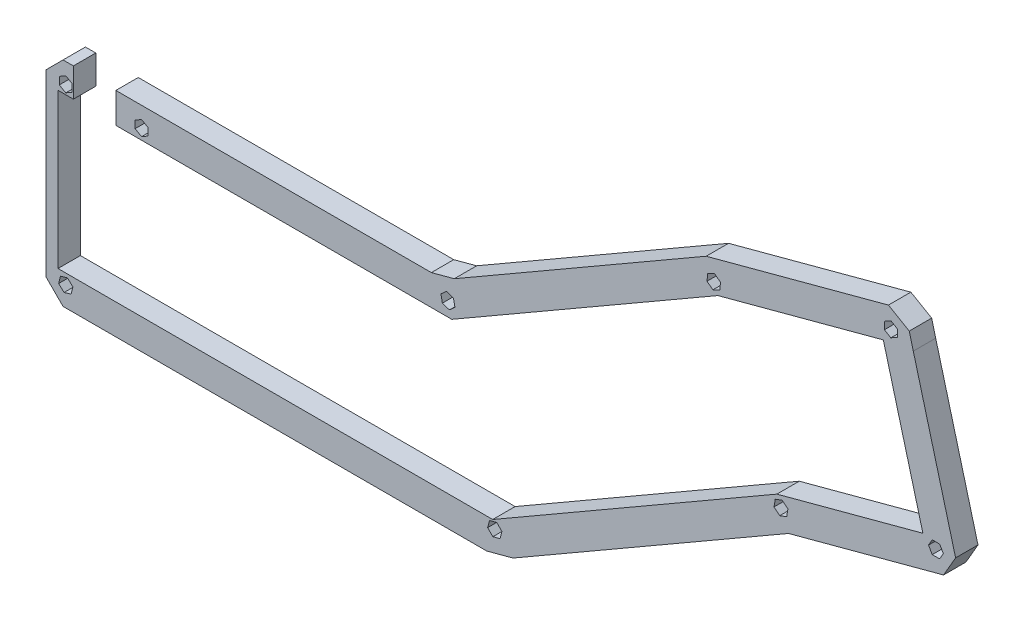
SolidWorks part; units mm, degrees
ref_plane "Plan de face" through (0, 0, 0) normal (0, 0, 1) x (1, 0, 0)
ref_plane "Plan de dessus" through (0, 0, 0) normal (0, 1, 0) x (1, 0, 0)
ref_plane "Plan de droite" through (0, 0, 0) normal (1, 0, 0) x (0, 0, -1)
sketch "Esquisse1" plane through (0, 0, 0) normal (0, 0, 1) x (1, 0, 0)
  line L0 (-73.9886, 18.0851) -> (-59.9886, 18.0851) construction
  line L1 (-73.9886, 37.0851) -> (-59.9886, 37.0851) construction
  line L2 (-73.9886, 37.0851) -> (-73.9886, 23.0851) construction
  line L3 (-73.9886, 23.0851) -> (-59.9886, 23.0851) construction
  line L4 (-59.9886, 37.0851) -> (-59.9886, 23.0851) construction
  line L5 (-73.9886, 18.0851) -> (-73.9886, 4.0851) construction
  line L6 (-73.9886, 4.0851) -> (-59.9886, 4.0851) construction
  line L7 (-59.9886, 18.0851) -> (-59.9886, 4.0851) construction
  line L8 (-73.9886, -0.9149) -> (-59.9886, -0.9149) construction
  line L9 (-73.9886, -0.9149) -> (-73.9886, -14.9149) construction
  line L10 (-73.9886, -14.9149) -> (-59.9886, -14.9149) construction
  line L11 (-59.9886, -0.9149) -> (-59.9886, -14.9149) construction
  line L12 (-73.9886, 37.0851) -> (-73.9886, 18.0851) construction
  line L13 (-54.9886, 18.0851) -> (-40.9886, 18.0851) construction
  line L14 (-54.9886, 37.0851) -> (-40.9886, 37.0851) construction
  line L15 (-54.9886, 37.0851) -> (-54.9886, 23.0851) construction
  line L16 (-54.9886, 23.0851) -> (-40.9886, 23.0851) construction
  line L17 (-40.9886, 37.0851) -> (-40.9886, 23.0851) construction
  line L18 (-54.9886, 18.0851) -> (-54.9886, 4.0851) construction
  line L19 (-54.9886, 4.0851) -> (-40.9886, 4.0851) construction
  line L20 (-40.9886, 18.0851) -> (-40.9886, 4.0851) construction
  line L21 (-54.9886, -0.9149) -> (-40.9886, -0.9149) construction
  line L22 (-54.9886, -0.9149) -> (-54.9886, -14.9149) construction
  line L23 (-54.9886, -14.9149) -> (-40.9886, -14.9149) construction
  line L24 (-40.9886, -0.9149) -> (-40.9886, -14.9149) construction
  line L25 (-54.9886, 37.0851) -> (-54.9886, 18.0851) construction
  line L26 (-35.9886, 18.0851) -> (-21.9886, 18.0851) construction
  line L27 (-35.9886, 37.0851) -> (-21.9886, 37.0851) construction
  line L28 (-35.9886, 37.0851) -> (-35.9886, 23.0851) construction
  line L29 (-35.9886, 23.0851) -> (-21.9886, 23.0851) construction
  line L30 (-21.9886, 37.0851) -> (-21.9886, 23.0851) construction
  line L31 (-35.9886, 18.0851) -> (-35.9886, 4.0851) construction
  line L32 (-35.9886, 4.0851) -> (-21.9886, 4.0851) construction
  line L33 (-21.9886, 18.0851) -> (-21.9886, 4.0851) construction
  line L34 (-35.9886, -0.9149) -> (-21.9886, -0.9149) construction
  line L35 (-35.9886, -0.9149) -> (-35.9886, -14.9149) construction
  line L36 (-35.9886, -14.9149) -> (-21.9886, -14.9149) construction
  line L37 (-21.9886, -0.9149) -> (-21.9886, -14.9149) construction
  line L38 (-35.9886, 37.0851) -> (-35.9886, 18.0851) construction
  line L39 (-16.9886, 18.0851) -> (-2.9886, 18.0851) construction
  line L40 (-16.9886, 37.0851) -> (-2.9886, 37.0851) construction
  line L41 (-16.9886, 37.0851) -> (-16.9886, 23.0851) construction
  line L42 (-16.9886, 23.0851) -> (-2.9886, 23.0851) construction
  line L43 (-2.9886, 37.0851) -> (-2.9886, 23.0851) construction
  line L44 (-16.9886, 18.0851) -> (-16.9886, 4.0851) construction
  line L45 (-16.9886, 4.0851) -> (-2.9886, 4.0851) construction
  line L46 (-2.9886, 18.0851) -> (-2.9886, 4.0851) construction
  line L47 (-16.9886, -0.9149) -> (-2.9886, -0.9149) construction
  line L48 (-16.9886, -0.9149) -> (-16.9886, -14.9149) construction
  line L49 (-16.9886, -14.9149) -> (-2.9886, -14.9149) construction
  line L50 (-2.9886, -0.9149) -> (-2.9886, -14.9149) construction
  line L51 (-16.9886, 37.0851) -> (-16.9886, 18.0851) construction
  line L52 (2.0114, 18.0851) -> (16.0114, 18.0851) construction
  line L53 (2.0114, 37.0851) -> (16.0114, 37.0851) construction
  line L54 (2.0114, 37.0851) -> (2.0114, 23.0851) construction
  line L55 (2.0114, 23.0851) -> (16.0114, 23.0851) construction
  line L56 (16.0114, 37.0851) -> (16.0114, 23.0851) construction
  line L57 (2.0114, 18.0851) -> (2.0114, 4.0851) construction
  line L58 (2.0114, 4.0851) -> (16.0114, 4.0851) construction
  line L59 (16.0114, 18.0851) -> (16.0114, 4.0851) construction
  line L60 (2.0114, -0.9149) -> (16.0114, -0.9149) construction
  line L61 (2.0114, -0.9149) -> (2.0114, -14.9149) construction
  line L62 (2.0114, -14.9149) -> (16.0114, -14.9149) construction
  line L63 (16.0114, -0.9149) -> (16.0114, -14.9149) construction
  line L64 (2.0114, 37.0851) -> (2.0114, 18.0851) construction
  line L65 (21.0114, 18.0851) -> (35.0114, 18.0851) construction
  line L66 (21.0114, 37.0851) -> (35.0114, 37.0851) construction
  line L67 (21.0114, 37.0851) -> (21.0114, 23.0851) construction
  line L68 (21.0114, 23.0851) -> (35.0114, 23.0851) construction
  line L69 (35.0114, 37.0851) -> (35.0114, 23.0851) construction
  line L70 (21.0114, 18.0851) -> (21.0114, 4.0851) construction
  line L71 (21.0114, 4.0851) -> (35.0114, 4.0851) construction
  line L72 (35.0114, 18.0851) -> (35.0114, 4.0851) construction
  line L73 (21.0114, -0.9149) -> (35.0114, -0.9149) construction
  line L74 (21.0114, -0.9149) -> (21.0114, -14.9149) construction
  line L75 (21.0114, -14.9149) -> (35.0114, -14.9149) construction
  line L76 (35.0114, -0.9149) -> (35.0114, -14.9149) construction
  line L77 (21.0114, 37.0851) -> (21.0114, 18.0851) construction
  line L78 (40.0114, 18.0851) -> (54.0114, 18.0851) construction
  line L79 (40.0114, 37.0851) -> (54.0114, 37.0851) construction
  line L80 (40.0114, 37.0851) -> (40.0114, 23.0851) construction
  line L81 (40.0114, 23.0851) -> (54.0114, 23.0851) construction
  line L82 (54.0114, 37.0851) -> (54.0114, 23.0851) construction
  line L83 (40.0114, 18.0851) -> (40.0114, 4.0851) construction
  line L84 (40.0114, 4.0851) -> (54.0114, 4.0851) construction
  line L85 (54.0114, 18.0851) -> (54.0114, 4.0851) construction
  line L86 (40.0114, -0.9149) -> (54.0114, -0.9149) construction
  line L87 (40.0114, -0.9149) -> (40.0114, -14.9149) construction
  line L88 (40.0114, -14.9149) -> (54.0114, -14.9149) construction
  line L89 (54.0114, -0.9149) -> (54.0114, -14.9149) construction
  line L90 (40.0114, 37.0851) -> (40.0114, 18.0851) construction
  line L91 (-73.9886, 18.0851) -> (-54.9886, 18.0851) construction
  line L92 (56.0114, 20.0851) -> (56.7532, 18.8002) construction
  line L93 (38.0114, 39.0851) -> (56.0114, 39.0851) construction
  line L94 (56.0114, 39.0851) -> (56.0114, 21.0851) construction
  line L95 (38.0114, 21.0851) -> (56.0114, 21.0851) construction
  line L96 (38.0114, 39.0851) -> (38.0114, 21.0851) construction
  line L97 (19.0114, 39.0851) -> (37.0114, 39.0851) construction
  line L98 (37.0114, 39.0851) -> (37.0114, 21.0851) construction
  line L99 (19.0114, 21.0851) -> (37.0114, 21.0851) construction
  line L100 (19.0114, 39.0851) -> (19.0114, 21.0851) construction
  line L101 (79.4363, 55.512) -> (88.4363, 39.9235) construction
  line L102 (88.4363, 39.9235) -> (72.8478, 30.9235) construction
  line L103 (63.8478, 46.512) -> (72.8478, 30.9235) construction
  line L104 (79.4363, 55.512) -> (63.8478, 46.512) construction
  line L105 (62.9818, 46.012) -> (71.9818, 30.4235) construction
  line L106 (71.9818, 30.4235) -> (56.3933, 21.4235) construction
  line L107 (47.3933, 37.012) -> (56.3933, 21.4235) construction
  line L108 (62.9818, 46.012) -> (47.3933, 37.012) construction
  line L109 (164.5845, 60.0309) -> (148.9961, 51.0309) construction
  line L110 (62.2497, 43.2799) -> (71.7497, 26.8254) construction
  line L111 (78.7042, 52.7799) -> (88.2042, 36.3254) construction
  line L112 (95.1587, 62.2799) -> (104.6587, 45.8254) construction
  line L113 (111.6132, 71.7799) -> (121.1132, 55.3254) construction
  line L114 (128.0677, 81.2799) -> (137.5677, 64.8254) construction
  line L115 (144.5221, 90.7799) -> (154.0221, 74.3254) construction
  line L116 (148.9961, 51.0309) -> (157.6657, 36.0146) construction
  line L117 (69.1254, 3.371) -> (76.1254, -8.7534) construction
  line L118 (88.2497, -1.7534) -> (76.1254, -8.7534) construction
  line L119 (81.2497, 10.371) -> (88.2497, -1.7534) construction
  line L120 (81.2497, 10.371) -> (69.1254, 3.371) construction
  line L121 (59.6254, 19.8254) -> (66.6254, 7.7011) construction
  line L122 (78.7497, 14.7011) -> (66.6254, 7.7011) construction
  line L123 (71.7497, 26.8254) -> (78.7497, 14.7011) construction
  line L124 (50.1254, 36.2799) -> (57.1254, 24.1556) construction
  line L125 (69.2497, 31.1556) -> (57.1254, 24.1556) construction
  line L126 (62.2497, 43.2799) -> (69.2497, 31.1556) construction
  line L127 (62.2497, 43.2799) -> (50.1254, 36.2799) construction
  line L128 (71.7497, 26.8254) -> (59.6254, 19.8254) construction
  line L129 (85.5799, 12.871) -> (92.5799, 0.7466) construction
  line L130 (104.7042, 7.7466) -> (92.5799, 0.7466) construction
  line L131 (97.7042, 19.871) -> (104.7042, 7.7466) construction
  line L132 (97.7042, 19.871) -> (85.5799, 12.871) construction
  line L133 (76.0799, 29.3254) -> (83.0799, 17.2011) construction
  line L134 (95.2042, 24.2011) -> (83.0799, 17.2011) construction
  line L135 (88.2042, 36.3254) -> (95.2042, 24.2011) construction
  line L136 (66.5799, 45.7799) -> (73.5799, 33.6556) construction
  line L137 (85.7042, 40.6556) -> (73.5799, 33.6556) construction
  line L138 (78.7042, 52.7799) -> (85.7042, 40.6556) construction
  line L139 (78.7042, 52.7799) -> (66.5799, 45.7799) construction
  line L140 (88.2042, 36.3254) -> (76.0799, 29.3254) construction
  line L141 (102.0343, 22.371) -> (109.0343, 10.2466) construction
  line L142 (121.1587, 17.2466) -> (109.0343, 10.2466) construction
  line L143 (114.1587, 29.371) -> (121.1587, 17.2466) construction
  line L144 (114.1587, 29.371) -> (102.0343, 22.371) construction
  line L145 (92.5343, 38.8254) -> (99.5343, 26.7011) construction
  line L146 (111.6587, 33.7011) -> (99.5343, 26.7011) construction
  line L147 (104.6587, 45.8254) -> (111.6587, 33.7011) construction
  line L148 (83.0343, 55.2799) -> (90.0343, 43.1556) construction
  line L149 (102.1587, 50.1556) -> (90.0343, 43.1556) construction
  line L150 (95.1587, 62.2799) -> (102.1587, 50.1556) construction
  line L151 (95.1587, 62.2799) -> (83.0343, 55.2799) construction
  line L152 (104.6587, 45.8254) -> (92.5343, 38.8254) construction
  line L153 (118.4888, 31.871) -> (125.4888, 19.7466) construction
  line L154 (137.6132, 26.7466) -> (125.4888, 19.7466) construction
  line L155 (130.6132, 38.871) -> (137.6132, 26.7466) construction
  line L156 (130.6132, 38.871) -> (118.4888, 31.871) construction
  line L157 (108.9888, 48.3254) -> (115.9888, 36.2011) construction
  line L158 (128.1132, 43.2011) -> (115.9888, 36.2011) construction
  line L159 (121.1132, 55.3254) -> (128.1132, 43.2011) construction
  line L160 (99.4888, 64.7799) -> (106.4888, 52.6556) construction
  line L161 (118.6132, 59.6556) -> (106.4888, 52.6556) construction
  line L162 (111.6132, 71.7799) -> (118.6132, 59.6556) construction
  line L163 (111.6132, 71.7799) -> (99.4888, 64.7799) construction
  line L164 (121.1132, 55.3254) -> (108.9888, 48.3254) construction
  line L165 (134.9433, 41.371) -> (141.9433, 29.2466) construction
  line L166 (154.0677, 36.2466) -> (141.9433, 29.2466) construction
  line L167 (147.0677, 48.371) -> (154.0677, 36.2466) construction
  line L168 (147.0677, 48.371) -> (134.9433, 41.371) construction
  line L169 (125.4433, 57.8254) -> (132.4433, 45.7011) construction
  line L170 (144.5677, 52.7011) -> (132.4433, 45.7011) construction
  line L171 (137.5677, 64.8254) -> (144.5677, 52.7011) construction
  line L172 (115.9433, 74.2799) -> (122.9433, 62.1556) construction
  line L173 (135.0677, 69.1556) -> (122.9433, 62.1556) construction
  line L174 (128.0677, 81.2799) -> (135.0677, 69.1556) construction
  line L175 (128.0677, 81.2799) -> (115.9433, 74.2799) construction
  line L176 (137.5677, 64.8254) -> (125.4433, 57.8254) construction
  line L177 (151.7281, 50.2988) -> (158.3978, 38.7466) construction
  line L178 (170.5221, 45.7466) -> (158.3978, 38.7466) construction
  line L179 (163.8525, 57.2988) -> (170.5221, 45.7466) construction
  line L180 (163.8525, 57.2988) -> (151.7281, 50.2988) construction
  line L181 (141.8978, 67.3254) -> (148.8978, 55.2011) construction
  line L182 (161.0221, 62.2011) -> (148.8978, 55.2011) construction
  line L183 (154.0221, 74.3254) -> (161.0221, 62.2011) construction
  line L184 (132.3978, 83.7799) -> (139.3978, 71.6556) construction
  line L185 (151.5221, 78.6556) -> (139.3978, 71.6556) construction
  line L186 (144.5221, 90.7799) -> (151.5221, 78.6556) construction
  line L187 (144.5221, 90.7799) -> (132.3978, 83.7799) construction
  line L188 (154.0221, 74.3254) -> (141.8978, 67.3254) construction
  line L189 (173.2542, 45.0146) -> (157.6657, 36.0146) construction
  line L190 (164.5845, 60.0309) -> (173.2542, 45.0146) construction
  line L191 (178.3169, 34.0986) -> (169.0534, 56.4627) construction
  line L192 (169.6903, 62.1458) -> (174.1781, 45.3972) construction
  line L193 (174.1781, 45.3972) -> (191.5647, 50.056) construction
  line L194 (187.077, 66.8045) -> (191.5647, 50.056) construction
  line L195 (162.1337, 98.0749) -> (167.0513, 79.7223) construction
  line L196 (169.6903, 62.1458) -> (187.077, 66.8045) construction
  line L197 (167.0513, 79.7223) -> (180.5742, 83.3457) construction
  line L198 (162.1337, 98.0749) -> (175.6567, 101.6983) construction
  line L199 (162.1337, 98.0749) -> (165.7572, 84.5519) construction
  line L200 (165.7572, 84.5519) -> (179.2801, 88.1754) construction
  line L201 (175.6567, 101.6983) -> (179.2801, 88.1754) construction
  line L202 (167.0513, 79.7223) -> (170.6747, 66.1993) construction
  line L203 (170.6747, 66.1993) -> (184.1977, 69.8228) construction
  line L204 (180.5742, 83.3457) -> (184.1977, 69.8228) construction
  line L205 (172.1398, 60.7315) -> (185.6628, 64.355) construction
  line L206 (172.1398, 60.7315) -> (175.5923, 47.8467) construction
  line L207 (175.5923, 47.8467) -> (189.1152, 51.4702) construction
  line L208 (185.6628, 64.355) -> (189.1152, 51.4702) construction
  line L209 (185.4038, 84.6398) -> (198.9268, 88.2633) construction
  line L210 (180.4863, 102.9924) -> (194.0092, 106.6159) construction
  line L211 (180.4863, 102.9924) -> (184.1097, 89.4695) construction
  line L212 (184.1097, 89.4695) -> (197.6327, 93.0929) construction
  line L213 (194.0092, 106.6159) -> (197.6327, 93.0929) construction
  line L214 (185.4038, 84.6398) -> (189.0273, 71.1169) construction
  line L215 (189.0273, 71.1169) -> (202.5503, 74.7403) construction
  line L216 (198.9268, 88.2633) -> (202.5503, 74.7403) construction
  line L217 (190.4924, 65.6491) -> (204.0154, 69.2726) construction
  line L218 (190.4924, 65.6491) -> (193.9449, 52.7643) construction
  line L219 (193.9449, 52.7643) -> (207.4678, 56.3878) construction
  line L220 (204.0154, 69.2726) -> (207.4678, 56.3878) construction
  line L221 (188.0429, 67.0633) -> (192.5307, 50.3148) construction
  line L222 (192.5307, 50.3148) -> (209.9173, 54.9735) construction
  line L223 (205.4296, 71.7221) -> (209.9173, 54.9735) construction
  line L224 (180.4863, 102.9924) -> (185.4038, 84.6398) construction
  line L225 (188.0429, 67.0633) -> (205.4296, 71.7221) construction
  line L226 (203.7564, 89.5574) -> (217.2794, 93.1809) construction
  line L227 (198.8389, 107.91) -> (212.3618, 111.5335) construction
  line L228 (198.8389, 107.91) -> (202.4623, 94.387) construction
  line L229 (202.4623, 94.387) -> (215.9853, 98.0105) construction
  line L230 (212.3618, 111.5335) -> (215.9853, 98.0105) construction
  line L231 (203.7564, 89.5574) -> (207.3799, 76.0344) construction
  line L232 (207.3799, 76.0344) -> (220.9029, 79.6579) construction
  line L233 (217.2794, 93.1809) -> (220.9029, 79.6579) construction
  line L234 (208.845, 70.5667) -> (222.368, 74.1901) construction
  line L235 (208.845, 70.5667) -> (212.2975, 57.6819) construction
  line L236 (212.2975, 57.6819) -> (225.8204, 61.3053) construction
  line L237 (222.368, 74.1901) -> (225.8204, 61.3053) construction
  line L238 (206.3955, 71.9809) -> (210.8833, 55.2324) construction
  line L239 (210.8833, 55.2324) -> (228.2699, 59.8911) construction
  line L240 (223.7822, 76.6396) -> (228.2699, 59.8911) construction
  line L241 (198.8389, 107.91) -> (203.7564, 89.5574) construction
  line L242 (206.3955, 71.9809) -> (223.7822, 76.6396) construction
  line L243 (167.0513, 79.7223) -> (185.4038, 84.6398) construction
  line L244 (38.0114, 20.0851) -> (56.0114, 20.0851) construction
  line L245 (56.0114, 20.0851) -> (56.0114, 2.0851) construction
  line L246 (38.0114, 2.0851) -> (56.0114, 2.0851) construction
  line L247 (38.0114, 20.0851) -> (38.0114, 2.0851) construction
  line L248 (72.4818, 29.5575) -> (56.8933, 20.5575) construction
  line L249 (56.8933, 20.5575) -> (65.8933, 4.969) construction
  line L250 (81.4818, 13.969) -> (65.8933, 4.969) construction
  line L251 (72.4818, 29.5575) -> (81.4818, 13.969) construction
  line L252 (56.8933, 20.5575) -> (57.6111, 19.3142) construction
  line L253 (164.6018, 81.1365) -> (169.2605, 63.7498) construction
  line L254 (169.2605, 63.7498) -> (186.6472, 68.4086) construction
  line L255 (181.9884, 85.7952) -> (186.6472, 68.4086) construction
  line L256 (164.6018, 81.1365) -> (181.9884, 85.7952) construction
  line L257 (154.7542, 77.0575) -> (163.7542, 61.469) construction
  line L258 (163.7542, 61.469) -> (148.1657, 52.469) construction
  line L259 (139.1657, 68.0575) -> (148.1657, 52.469) construction
  line L260 (154.7542, 77.0575) -> (139.1657, 68.0575) construction
  line L261 (196.3894, 109.3242) -> (213.776, 113.983) construction
  line L262 (-94.7538, 35.7952) -> (-76.7538, 35.7952) construction
  line L263 (-94.7538, 35.7952) -> (-94.7538, 2.7952) construction
  line L264 (-94.7538, 2.7952) -> (-76.7538, 2.7952) construction
  line L265 (-76.7538, 35.7952) -> (-76.7538, 2.7952) construction
  line L266 (213.776, 113.983) -> (218.4348, 96.5963) construction
  line L267 (201.0481, 91.9375) -> (218.4348, 96.5963) construction
  line L268 (196.3894, 109.3242) -> (201.0481, 91.9375) construction
  line L269 (-75.9886, -16.9149) -> (-57.9886, -16.9149) construction
  line L270 (-57.9886, 1.0851) -> (-57.9886, -16.9149) construction
  line L271 (-75.9886, 1.0851) -> (-57.9886, 1.0851) construction
  line L272 (-75.9886, 1.0851) -> (-75.9886, -16.9149) construction
  line L273 (38.0114, -16.9149) -> (56.0114, -16.9149) construction
  line L274 (56.0114, 1.0851) -> (56.0114, -16.9149) construction
  line L275 (38.0114, 1.0851) -> (56.0114, 1.0851) construction
  line L276 (38.0114, 1.0851) -> (38.0114, -16.9149) construction
  line L277 (-75.9886, 39.0851) -> (-57.9886, 39.0851) construction
  line L278 (-57.9886, 39.0851) -> (-57.9886, 21.0851) construction
  line L279 (-75.9886, 21.0851) -> (-57.9886, 21.0851) construction
  line L280 (-75.9886, 39.0851) -> (-75.9886, 21.0851) construction
  line L281 (145.2542, 93.512) -> (129.6657, 84.512) construction
  line L282 (129.6657, 84.512) -> (138.6657, 68.9235) construction
  line L283 (154.2542, 77.9235) -> (138.6657, 68.9235) construction
  line L284 (145.2542, 93.512) -> (154.2542, 77.9235) construction
  line L285 (223.4353, 116.5711) -> (228.0941, 99.1845) construction
  line L286 (148.2159, 106.7689) -> (211.1879, 123.6422) construction
  line L287 (177.5508, 35.9482) -> (235.6877, 51.5259) construction
  line L288 (177.5508, 35.9482) -> (72.9989, -24.4149) construction
  line L289 (-95.7538, -26.9149) -> (63.6687, -26.9149) construction
  line L290 (-100.7538, 35.7952) -> (-100.7538, -21.9149) construction
  line L291 (-75.9886, 49.0851) -> (43.3046, 49.0851) construction
  line L292 (148.2159, 106.7689) -> (52.6347, 51.5851) construction
  line L293 (-75.9886, 49.0851) -> (-57.9886, 49.0851) construction
  line L294 (140.2542, 102.1722) -> (124.6657, 93.1722) construction
  line L295 (193.8012, 118.9835) -> (211.1879, 123.6422) construction
  line L296 (213.4714, 45.5731) -> (230.8581, 50.2318) construction
  line L297 (38.0114, -26.9149) -> (38.0114, -85.4624) construction
  line L298 (178.2542, 36.3543) -> (162.6657, 27.3543) construction
  line L299 (38.0114, -26.9149) -> (56.0114, -26.9149) construction
  line L300 (-100.7538, 2.7952) -> (-100.7538, -38.0419) construction
  line L301 (-100.7538, 35.7952) -> (-100.7538, 2.7952) construction
  line L302 (-75.9886, 49.0851) -> (-95.7538, 49.0851) construction
  line L303 (-100.7538, 44.0851) -> (-100.7538, 35.7952) construction
  line L304 (211.1879, 123.6422) -> (216.0693, 124.9502) construction
  line L305 (222.1671, 121.4078) -> (223.4353, 116.5711) construction
  line L306 (228.0941, 99.1845) -> (239.2233, 57.6497) construction
  line L307 (216.0693, 124.9502) -> (222.1671, 121.4078) construction
  line L308 (235.6877, 51.5259) -> (239.2233, 57.6497) construction
  line L309 (63.6687, -26.9149) -> (72.9989, -24.4149) construction
  line L310 (52.6347, 51.5851) -> (43.3046, 49.0851) construction
  line L311 (-95.7538, 49.0851) -> (-100.7538, 44.0851) construction
  line L312 (-100.7538, -21.9149) -> (-95.7538, -26.9149) construction
  line L313 (-95.7538, 49.0851) -> (-95.7538, 44.0851) construction
  line L314 (-95.7538, 44.0851) -> (-100.7538, 44.0851) construction
  line L315 (-95.7538, -26.9149) -> (-95.7538, -21.9149) construction
  line L316 (68.3338, -25.6649) -> (67.0397, -20.8353) construction
  line L317 (47.9697, 50.3351) -> (49.2637, 45.5055) construction
  line L318 (177.5508, 35.9482) -> (175.6374, 40.5676) construction
  line L319 (148.2159, 106.7689) -> (150.1293, 102.1495) construction
  line L320 (239.2233, 57.6497) -> (234.4455, 56.3695) construction
  line L321 (216.0693, 124.9502) -> (217.3634, 120.1206) construction
  line L322 (-75.9886, 49.5851) -> (43.2388, 49.5851) construction
  line L323 (52.4417, 52.051) -> (43.2388, 49.5851) construction
  line L324 (148.0229, 107.2348) -> (52.4417, 52.051) construction
  line L325 (148.0229, 107.2348) -> (211.0584, 124.1252) construction
  line L326 (211.0584, 124.1252) -> (216.1407, 125.487) construction
  line L327 (216.1407, 125.487) -> (222.598, 121.7357) construction
  line L328 (222.598, 121.7357) -> (223.9186, 116.6993) construction
  line L329 (223.9186, 116.6993) -> (228.577, 99.3139) construction
  line L330 (228.577, 99.3139) -> (239.7598, 57.579) construction
  line L331 (236.0172, 51.0966) -> (239.7598, 57.579) construction
  line L332 (177.7438, 35.4823) -> (236.0172, 51.0966) construction
  line L333 (177.7438, 35.4823) -> (73.1918, -24.8808) construction
  line L334 (63.7346, -27.4149) -> (73.1918, -24.8808) construction
  line L335 (-95.9609, -27.4149) -> (63.7346, -27.4149) construction
  line L336 (-101.2538, -22.122) -> (-95.9609, -27.4149) construction
  line L337 (-101.2538, 35.7952) -> (-101.2538, -22.122) construction
  line L338 (-101.2538, 44.2922) -> (-101.2538, 35.7952) construction
  line L339 (-95.9609, 49.5851) -> (-101.2538, 44.2922) construction
  line L340 (-75.9886, 49.5851) -> (-76.7538, 49.5851) construction
  line L341 (2.0114, 40.0851) -> (52.7161, 40.0851)
  line L342 (151.6898, 98.3823) -> (50.7161, 40.0851)
  line L343 (-95.7538, 44.0851) -> (-63.3184, 44.0851) construction
  line L344 (-98.6986, -17.9149) -> (66.2572, -17.9149)
  line L345 (174.0769, 44.3349) -> (66.2572, -17.9149)
  line L346 (174.0769, 44.3349) -> (229.4947, 59.184)
  line L347 (214.4832, 115.2077) -> (229.4947, 59.184)
  line L348 (151.6898, 98.3823) -> (214.4832, 115.2077)
  line L349 (225.2657, 74.9666) -> (228.7182, 62.0818) construction
  line L350 (176.3687, 44.949) -> (189.8917, 48.5724) construction
  line L351 (89.7497, -4.3515) -> (77.6254, -11.3515) construction
  line L352 (-54.9886, -17.9149) -> (-40.9886, -17.9149) construction
  line L353 (-92.8618, 49.5851) -> (-76.7538, 49.5851) construction
  line L354 (2.0114, 40.0851) -> (16.0114, 40.0851) construction
  line L355 (77.2042, 55.378) -> (65.0799, 48.378) construction
  line L356 (179.7098, 105.8902) -> (193.2328, 109.5137) construction
  line L357 (2.0114, 40.0851) -> (-76.7538, 40.0851)
  line L358 (-76.7538, 40.0851) -> (-76.7538, 54.5851) construction
  line L359 (-92.8618, 54.5851) -> (-76.7538, 54.5851) construction
  line L360 (-98.6986, 40.6556) -> (-94.8608, 40.6556)
  line L361 (-94.8608, 40.6556) -> (-92.8618, 40.6556)
  line L362 (-94.8608, 49.5851) -> (-95.9609, 49.5851) construction
  line L363 (-66.9886, 37.0851) -> (-66.9886, 49.5851) construction
  line L364 (-75.9886, 49.5851) -> (-95.9609, 49.5851) construction
  line L365 (-92.8618, 40.6556) -> (-92.8618, 54.5851) construction
  line L366 (-76.7538, 39.0851) -> (-97.0101, 39.0851) construction
  line L367 (-76.7538, 39.0851) -> (-76.7538, 1.0851) construction
  line L368 (-76.7538, 1.0851) -> (-97.0101, 1.0851) construction
  line L369 (-97.0101, 39.0851) -> (-97.0101, 1.0851) construction
  line L370 (-92.8618, 49.5851) -> (-94.8608, 49.5851) construction
  line L371 (-98.6986, 40.6556) -> (-98.6986, -17.9149)
  line L372 (-75.9886, 54.5851) -> (-76.7538, 54.5851) construction
  line L373 (-75.9886, 54.5851) -> (42.5805, 54.5851) construction
  line L374 (50.5118, 56.7103) -> (42.5805, 54.5851) construction
  line L375 (146.093, 111.8941) -> (50.5118, 56.7103) construction
  line L376 (146.093, 111.8941) -> (209.7644, 128.9548) construction
  line L377 (209.7644, 128.9548) -> (216.8547, 130.8547) construction
  line L378 (216.8547, 130.8547) -> (226.9072, 125.0148) construction
  line L379 (226.9072, 125.0148) -> (228.7517, 117.9804) construction
  line L380 (228.7517, 117.9804) -> (233.4066, 100.608) construction
  line L381 (233.4066, 100.608) -> (245.1255, 56.8726) construction
  line L382 (239.3118, 46.803) -> (245.1255, 56.8726) construction
  line L383 (179.6737, 30.823) -> (239.3118, 46.803) construction
  line L384 (179.6737, 30.823) -> (75.1218, -29.5401) construction
  line L385 (64.3928, -32.4149) -> (75.1218, -29.5401) construction
  line L386 (-98.0319, -32.4149) -> (64.3928, -32.4149) construction
  line L387 (-106.2538, -24.1931) -> (-98.0319, -32.4149) construction
  line L388 (-106.2538, 35.7952) -> (-106.2538, -24.1931) construction
  line L389 (-106.2538, 46.3633) -> (-106.2538, 35.7952) construction
  line L390 (-98.0319, 54.5851) -> (-106.2538, 46.3633) construction
  line L391 (-94.8608, 54.5851) -> (-98.0319, 54.5851) construction
  line L392 (-92.8618, 54.5851) -> (-94.8608, 54.5851) construction
  line L394 (-76.7538, 54.5851) -> (-92.8618, 54.5851) construction
  line L396 (-92.8618, 51.5851) -> (-94.8608, 51.5851)
  line L397 (-94.8608, 51.5851) -> (-96.7893, 51.5851)
  line L398 (-96.7893, 51.5851) -> (-103.2538, 45.1206)
  line L399 (-103.2538, 45.1206) -> (-103.2538, 35.7952)
  line L400 (-103.2538, 35.7952) -> (-103.2538, -22.9504)
  line L401 (-103.2538, -22.9504) -> (-96.7893, -29.4149)
  line L402 (-96.7893, -29.4149) -> (63.9979, -29.4149)
  line L403 (63.9979, -29.4149) -> (73.9638, -26.7445)
  line L404 (178.5158, 33.6186) -> (73.9638, -26.7445)
  line L405 (178.5158, 33.6186) -> (237.335, 49.3791)
  line L406 (237.335, 49.3791) -> (241.9061, 57.2965)
  line L407 (230.5089, 99.8315) -> (241.9061, 57.2965)
  line L408 (225.8519, 117.2117) -> (230.5089, 99.8315)
  line L409 (224.3217, 123.0473) -> (225.8519, 117.2117)
  line L410 (216.4263, 127.634) -> (224.3217, 123.0473)
  line L411 (210.5408, 126.057) -> (216.4263, 127.634)
  line L412 (147.2509, 109.0986) -> (210.5408, 126.057)
  line L413 (147.2509, 109.0986) -> (51.6698, 53.9147)
  line L414 (51.6698, 53.9147) -> (42.9755, 51.5851)
  line L415 (-75.9886, 51.5851) -> (42.9755, 51.5851)
  line L416 (-75.9886, 51.5851) -> (-76.7538, 51.5851)
  line L417 (-76.7538, 48.6361) -> (-76.7538, 40.0851)
  line L418 (-92.8618, 48.6361) -> (-92.8618, 40.6556)
  line L419 (-76.7538, 50.2988) -> (-76.7538, 48.6361)
  line L420 (-92.8618, 50.2988) -> (-92.8618, 48.6361)
  line L421 (-97.4756, -23.6367) -> (-94.032, -20.1931) construction
  line L422 (-93.3188, 42.6793) -> (-93.3188, 45.491)
  line L423 (-93.3188, 45.491) -> (-95.7538, 46.8968)
  line L424 (-95.7538, 46.8968) -> (-98.1888, 45.491)
  line L425 (-98.1888, 45.491) -> (-98.1888, 42.6793)
  line L426 (-98.1888, 42.6793) -> (-95.7538, 41.2734)
  line L427 (-95.7538, 41.2734) -> (-93.3188, 42.6793)
  line L428 (-64.5536, 45.491) -> (-66.9886, 46.8968)
  line L429 (-66.9886, 46.8968) -> (-69.4236, 45.491)
  line L430 (-69.4236, 45.491) -> (-69.4236, 42.6793)
  line L431 (-69.4236, 42.6793) -> (-66.9886, 41.2734)
  line L432 (-66.9886, 41.2734) -> (-64.5536, 42.6793)
  line L433 (-64.5536, 42.6793) -> (-64.5536, 45.491)
  line L434 (51.9317, 44.6181) -> (51.3662, 47.3724)
  line L435 (51.3662, 47.3724) -> (48.6982, 48.2597)
  line L436 (48.6982, 48.2597) -> (46.5957, 46.3928)
  line L437 (46.5957, 46.3928) -> (47.1613, 43.6386)
  line L438 (47.1613, 43.6386) -> (49.8293, 42.7512)
  line L439 (49.8293, 42.7512) -> (51.9317, 44.6181)
  line L440 (152.7035, 103.2806) -> (150.4369, 104.9443)
  line L441 (150.4369, 104.9443) -> (147.8627, 103.8133)
  line L442 (147.8627, 103.8133) -> (147.5551, 101.0185)
  line L443 (147.5551, 101.0185) -> (149.8217, 99.3547)
  line L444 (149.8217, 99.3547) -> (152.3959, 100.4857)
  line L445 (152.3959, 100.4857) -> (152.7035, 103.2806)
  line L446 (219.7717, 118.6694) -> (219.8243, 121.4806)
  line L447 (219.8243, 121.4806) -> (217.416, 122.9318)
  line L448 (217.416, 122.9318) -> (214.9551, 121.5717)
  line L449 (214.9551, 121.5717) -> (214.9025, 118.7605)
  line L450 (214.9025, 118.7605) -> (217.3108, 117.3094)
  line L451 (217.3108, 117.3094) -> (219.7717, 118.6694)
  line L452 (237.2572, 56.3695) -> (235.8513, 58.8045)
  line L453 (235.8513, 58.8045) -> (233.0396, 58.8045)
  line L454 (233.0396, 58.8045) -> (231.6338, 56.3695)
  line L455 (231.6338, 56.3695) -> (233.0396, 53.9345)
  line L456 (233.0396, 53.9345) -> (235.8513, 53.9345)
  line L457 (235.8513, 53.9345) -> (237.2572, 56.3695)
  line L458 (178.2704, 41.554) -> (176.0996, 43.341)
  line L459 (176.0996, 43.341) -> (173.4666, 42.3546)
  line L460 (173.4666, 42.3546) -> (173.0044, 39.5812)
  line L461 (173.0044, 39.5812) -> (175.1751, 37.7942)
  line L462 (175.1751, 37.7942) -> (177.8081, 38.7806)
  line L463 (177.8081, 38.7806) -> (178.2704, 41.554)
  line L464 (69.7556, -20.1075) -> (67.7674, -18.1194)
  line L465 (67.7674, -18.1194) -> (65.0515, -18.8471)
  line L466 (65.0515, -18.8471) -> (64.3238, -21.563)
  line L467 (64.3238, -21.563) -> (66.312, -23.5512)
  line L468 (66.312, -23.5512) -> (69.0279, -22.8234)
  line L469 (69.0279, -22.8234) -> (69.7556, -20.1075)
  line L470 (-92.8618, 50.2988) -> (-92.8618, 51.5851)
  line L471 (-93.0572, -21.1185) -> (-95.0952, -19.1814)
  line L472 (-95.0952, -19.1814) -> (-97.7917, -19.9778)
  line L473 (-97.7917, -19.9778) -> (-98.4503, -22.7113)
  line L474 (-98.4503, -22.7113) -> (-96.4124, -24.6484)
  line L475 (-96.4124, -24.6484) -> (-93.7158, -23.852)
  line L476 (-93.7158, -23.852) -> (-93.0572, -21.1185)
  line L477 (-76.7538, 51.5851) -> (-76.7538, 50.2988)
  line L479 (-76.7538, 51.5851) -> (-92.8618, 51.5851) construction
  circle A0 centre (-95.7538, 44.0851) radius 1.5 construction
  circle A1 centre (-95.7538, -21.9149) radius 1.5 construction
  circle A2 centre (67.0397, -20.8353) radius 1.5 construction
  circle A3 centre (49.2637, 45.5055) radius 1.5 construction
  circle A4 centre (175.6374, 40.5676) radius 1.5 construction
  circle A5 centre (150.1293, 102.1495) radius 1.5 construction
  circle A6 centre (234.4455, 56.3695) radius 1.5 construction
  circle A7 centre (217.3634, 120.1206) radius 1.5 construction
  circle A8 centre (-66.9886, 44.0851) radius 1.5 construction
  circle A9 centre (-95.7538, 44.0851) radius 2.435 construction
  circle A10 centre (-66.9886, 44.0851) radius 2.435 construction
  circle A11 centre (49.2637, 45.5055) radius 2.435 construction
  circle A12 centre (150.1293, 102.1495) radius 2.435 construction
  circle A13 centre (217.3634, 120.1206) radius 2.435 construction
  circle A14 centre (234.4455, 56.3695) radius 2.435 construction
  circle A15 centre (175.6374, 40.5676) radius 2.435 construction
  circle A16 centre (67.0397, -20.8353) radius 2.435 construction
  circle A17 centre (-95.7538, -21.9149) radius 2.435 construction
  point P304 (48.3046, 49.0851)
  point P305 (240.5174, 52.82)
  point P308 (68.6687, -26.9149)
  point P309 (-100.7538, -26.9149)
  point P311 (-100.7538, 49.0851)
  point P312 (220.8989, 126.2443)
  point P505 (-95.7538, -21.9149)
  dimension "D32" = 3
  dimension "D33" = 5
  dimension "D40" = 5
  dimension "D41" = 5
  dimension "D42" = 5
  dimension "D43" = 5
  dimension "D44" = 0.5
  dimension "D53" = 3
  dimension "D47" = 5
  dimension "D1" = 14
  dimension "D2" = 14
  dimension "D4" = 19
  dimension "D6" = 19
  dimension "D7" = 30
  dimension "D10" = 1
  dimension "D11" = 2
  dimension "D13" = 0.5
  dimension "D15" = 2
  dimension "D12" = 7.5
  dimension "D14" = 19
  dimension "D18" = 2
  dimension "D20" = 18
  dimension "D21" = 33
  dimension "D22" = 2
  dimension "D54" = 4.87
  dimension "D55" = 4.87
  dimension "D56" = 4.87
  dimension "D57" = 4.87
  dimension "D58" = 4.87
  dimension "D59" = 4.87
  dimension "D60" = 4.87
  dimension "D61" = 4.87
  dimension "D62" = 4.87
  dimension "D63" = 4.87
  dimension "D8" = 2
  dimension "D9" = 2
  dimension "D16" = 2
  dimension "D19" = 2
  dimension "D23" = 2
  dimension "D24" = 10
  dimension "D25" = 10
  dimension "D26" = 10
  dimension "D27" = 10
  dimension "D28" = 10
  dimension "D29" = 6
  dimension "D30" = 10
  dimension "D31" = 10
  dimension "D45" = 3
  dimension "D46" = 3
  dimension "D48" = 3
  dimension "D49" = 3
  dimension "D50" = 3
  dimension "D51" = 3
  dimension "D52" = 3
  dimension "D3" = 3
  dimension "D5" = 7
  dimension "D17" = 3
extrude "Boss.-Extru.1" add sketch "Esquisse1" along normal blind 8.5
